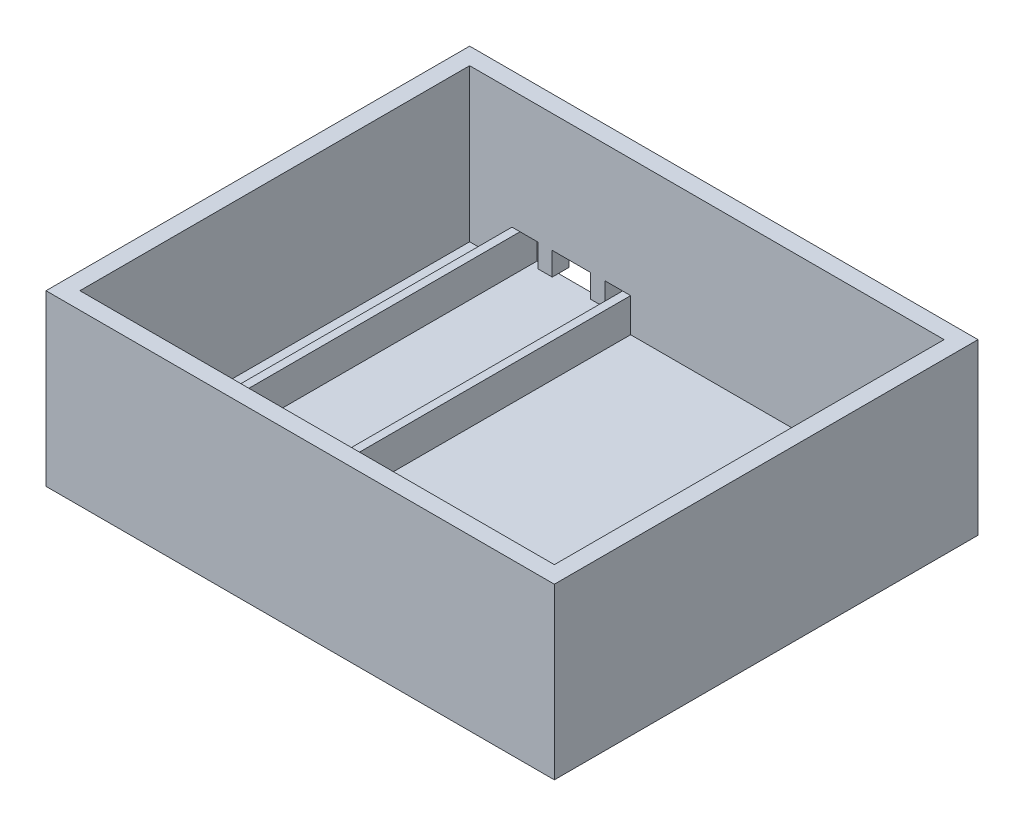
SolidWorks part; units mm, degrees
ref_plane "Front Plane" through (0, 0, 0) normal (0, 0, 1) x (1, 0, 0)
ref_plane "Top Plane" through (0, 0, 0) normal (0, 1, 0) x (1, 0, 0)
ref_plane "Right Plane" through (0, 0, 0) normal (1, 0, 0) x (0, 0, -1)
sketch "Sketch1" plane through (0, 0, 0) normal (0, 1, 0) x (1, 0, 0)
  line L1 (-70.5712, -39.9173) -> (49.4288, -39.9173)
  line L2 (-70.5712, -39.9173) -> (-70.5712, 60.0827)
  line L3 (-70.5712, 60.0827) -> (49.4288, 60.0827)
  line L4 (49.4288, -39.9173) -> (49.4288, 60.0827)
  dimension "D1" = 120
  dimension "D2" = 100
extrude "Boss-Extrude1" add sketch "Sketch1" along normal blind 40
sketch "Sketch2" plane through (0, 40, 0) normal (0, 1, 0) x (1, 0, 0)
  line L0 (49.4288, 60.0827) -> (-70.5712, 60.0827) construction
  line L1 (-66.5712, 56.0827) -> (45.4288, 56.0827)
  line L2 (-66.5712, 56.0827) -> (-66.5712, -35.9173)
  line L3 (-66.5712, -35.9173) -> (45.4288, -35.9173)
  line L4 (45.4288, 56.0827) -> (45.4288, -35.9173)
  line L5 (-70.5712, -39.9173) -> (49.4288, -39.9173) construction
  line L6 (-70.5712, 60.0827) -> (-70.5712, -39.9173) construction
  line L7 (49.4288, -39.9173) -> (49.4288, 60.0827) construction
  dimension "D1" = 4
  dimension "D2" = 4
  dimension "D3" = 4
  dimension "D4" = 4
extrude "Cut-Extrude1" cut sketch "Sketch2" against normal blind 36
sketch "Sketch3" plane through (0, 4, 0) normal (0, 1, 0) x (1, 0, 0)
  line L0 (-66.5712, 56.0827) -> (-66.5712, -35.9173) construction
  line L1 (49.4288, 60.0827) -> (-70.5712, 60.0827) construction
  line L2 (-56.5712, 60.0827) -> (-28.5712, 60.0827)
  line L3 (-56.5712, 60.0827) -> (-56.5712, -9.9173)
  line L4 (-56.5712, -9.9173) -> (-28.5712, -9.9173)
  line L5 (-28.5712, 60.0827) -> (-28.5712, -9.9173)
  dimension "D1" = 28
  dimension "D2" = 70
  dimension "D3" = 10
extrude "Boss-Extrude3" add sketch "Sketch3" along normal blind 8
sketch "Sketch6" plane through (0, 0, 9.9173) normal (0, 0, 1) x (1, 0, 0)
  line L0 (-56.5712, 12) -> (-28.5712, 12) construction
  line L1 (-54.6743, 12) -> (-30.4643, 12)
  line L2 (-54.6743, 12) -> (-54.6743, 4)
  line L3 (-54.6743, 4) -> (-30.4643, 4)
  line L4 (-30.4643, 12) -> (-30.4643, 4)
  line L5 (-66.5712, 4) -> (45.4288, 4) construction
  dimension "D1" = 24.21
extrude "Cut-Extrude4" cut sketch "Sketch6" against normal blind 66
sketch "Sketch7" plane through (0, 0, -56.0827) normal (0, 0, 1) x (1, 0, 0)
  line L0 (-30.4643, 4) -> (-30.4643, 12) construction
  line L1 (-54.6743, 12) -> (-50.4743, 12)
  line L2 (-54.6743, 12) -> (-54.6743, 6.53)
  line L4 (-30.4643, 12) -> (-30.4643, 6.53)
  line L6 (-47.0743, 12) -> (-38.0743, 12)
  line L7 (-38.0743, 6.53) -> (-34.6643, 6.53)
  line L8 (-50.4743, 12) -> (-50.4743, 6.53)
  line L9 (-50.4743, 6.53) -> (-47.0743, 6.53)
  line L10 (-34.6643, 12) -> (-34.6643, 6.53)
  line L11 (-54.6743, 6.53) -> (-54.6743, 4)
  line L12 (-47.0743, 6.53) -> (-47.0743, 12)
  line L13 (-54.6743, 4) -> (-30.4643, 4)
  line L14 (-38.0743, 6.53) -> (-38.0743, 12)
  line L15 (-34.6643, 12) -> (-30.4643, 12)
  line L18 (-30.4643, 6.53) -> (-30.4643, 4)
  dimension "D2" = 4.2
  dimension "D3" = 4.2
  dimension "D4" = 9
  dimension "D5" = 3.4
extrude "Cut-Extrude6" cut sketch "Sketch7" against normal blind 66
